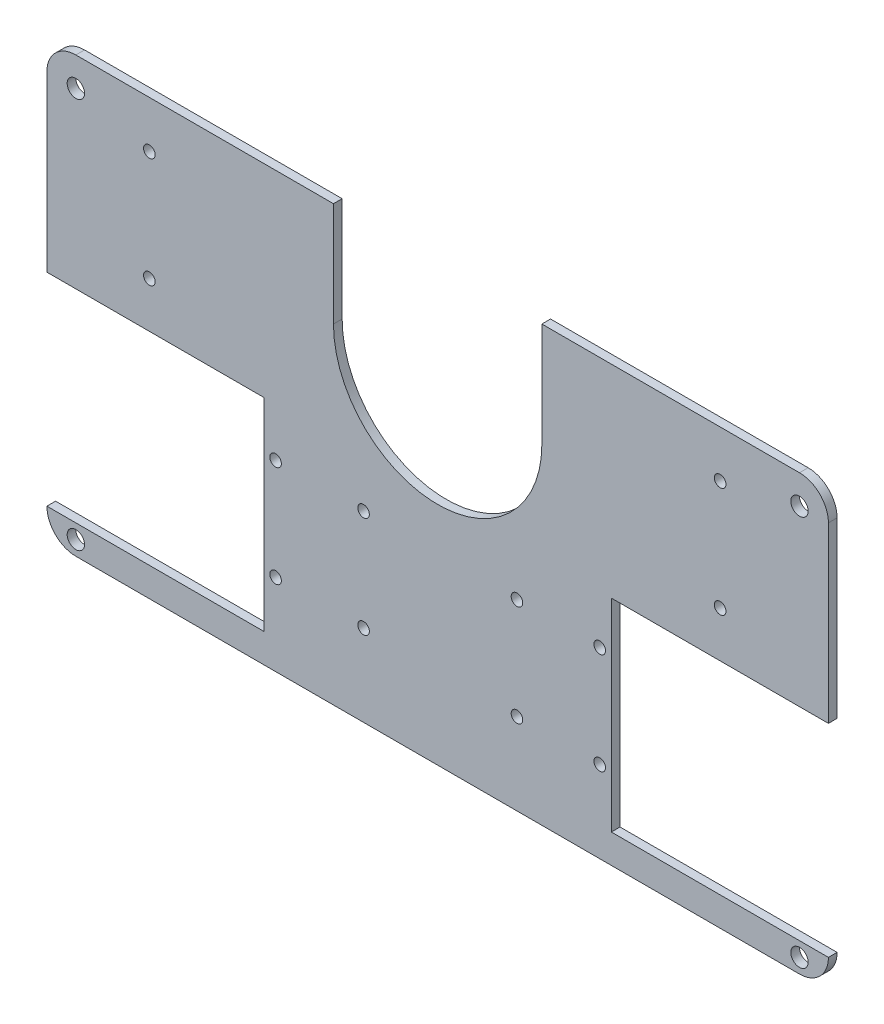
SolidWorks part; units mm, degrees
ref_plane "Front Plane" through (0, 0, 0) normal (0, 0, 1) x (1, 0, 0)
ref_plane "Top Plane" through (0, 0, 0) normal (0, 1, 0) x (1, 0, 0)
ref_plane "Right Plane" through (0, 0, 0) normal (1, 0, 0) x (0, 0, -1)
sketch "Esquisse1" plane through (0, 0, 0) normal (0, 0, 1) x (1, 0, 0)
  line L1 (10, 0) -> (99, 0)
  line L2 (0, -10) -> (0, -140)
  line L3 (10, -150) -> (260, -150)
  line L4 (270, -10) -> (270, -140)
  line L6 (99, 0) -> (99, -36)
  line L7 (171, -36) -> (171, 0)
  line L8 (171, 0) -> (260, 0)
  arc A0 (270, -10) -> (260, 0) centre (260, -10) ccw
  arc A1 (0, -10) -> (10, 0) centre (10, -10) cw
  arc A2 (270, -140) -> (260, -150) centre (260, -140) cw
  arc A3 (0, -140) -> (10, -150) centre (10, -140) ccw
  circle A4 centre (109.4, -121.7894) radius 2
  circle A5 centre (109.4, -121.7894) radius 2 construction
  circle A6 centre (109.4, -86.7894) radius 2
  circle A7 centre (109.4, -86.7894) radius 2 construction
  circle A8 centre (79, -121.7894) radius 2
  circle A9 centre (79, -86.7894) radius 2
  circle A10 centre (79, -86.7894) radius 2 construction
  circle A11 centre (79, -121.7894) radius 2 construction
  circle A12 centre (162.4, -121.7894) radius 2
  circle A13 centre (162.4, -86.7894) radius 2
  circle A14 centre (191, -121.7894) radius 2
  circle A16 centre (162.4, -121.7894) radius 2 construction
  circle A17 centre (191, -121.7894) radius 2 construction
  circle A18 centre (162.4, -86.7894) radius 2 construction
  circle A19 centre (191, -86.7894) radius 2
  circle A20 centre (191, -86.7894) radius 2 construction
  arc A21 (99, -36) -> (171, -36) centre (135, -36) ccw
  circle A22 centre (35.4, -16.1912) radius 2
  circle A23 centre (35.4, -54.1912) radius 2
  circle A24 centre (35.4, -16.1912) radius 2 construction
  circle A25 centre (35.4, -54.1912) radius 2 construction
  circle A26 centre (35.4, -16.1912) radius 2 construction
  circle A27 centre (232.6, -16.1912) radius 2
  circle A28 centre (232.6, -54.1912) radius 2
  circle A29 centre (232.6, -16.1912) radius 2 construction
  circle A30 centre (232.6, -54.1912) radius 2 construction
  point P7 (270, 0)
  point P10 (0, 0)
  point P15 (0, -150)
  dimension "D3" = 10
  dimension "D4" = 10
  dimension "D5" = 4
  dimension "D6" = 4
  dimension "D7" = 4
  dimension "D8" = 4
  dimension "D9" = 4
  dimension "D10" = 4
  dimension "D11" = 4
  dimension "D12" = 4
  dimension "D14" = 36
  dimension "D1" = 270
  dimension "D2" = 150
  dimension "D13" = 36
extrude "Boss.-Extru.1" add sketch "Esquisse1" along normal blind 3
sketch "Esquisse2" plane through (0, 0, 3) normal (0, 0, 1) x (1, 0, 0)
  line L1 (0, -140) -> (75, -140)
  line L2 (0, -140) -> (0, -70)
  line L3 (0, -70) -> (75, -70)
  line L4 (75, -140) -> (75, -70)
  line L5 (270, -140) -> (195, -140)
  line L6 (270, -140) -> (270, -70)
  line L7 (270, -70) -> (195, -70)
  line L8 (195, -140) -> (195, -70)
  line L9 (0, -10) -> (0, -140) construction
  line L10 (10, -150) -> (260, -150) construction
  line L11 (270, -140) -> (270, -10) construction
  dimension "D1" = 70
  dimension "D2" = 70
  dimension "D3" = 75
  dimension "D4" = 75
  dimension "D5" = 10
  dimension "D6" = 10
extrude "Enlèv. mat.-Extru.1" cut sketch "Esquisse2" against normal blind 3
sketch "Esquisse3" plane through (0, 0, 3) normal (0, 0, 1) x (1, 0, 0)
  line L0 (0, -10) -> (0, -70) construction
  line L1 (0, -140) -> (75, -140) construction
  line L2 (270, -70) -> (270, -10) construction
  line L4 (195, -140) -> (270, -140) construction
  circle A0 centre (10, -10) radius 3
  circle A1 centre (260, -10) radius 3
  circle A2 centre (260, -145) radius 3
  circle A3 centre (10, -145) radius 3
  dimension "D1" = 6
  dimension "D2" = 6
  dimension "D3" = 6
  dimension "D4" = 6
  dimension "D5" = 10
  dimension "D6" = 5
  dimension "D7" = 10
  dimension "D8" = 5
extrude "Enlèv. mat.-Extru.2" cut sketch "Esquisse3" against normal blind 10
